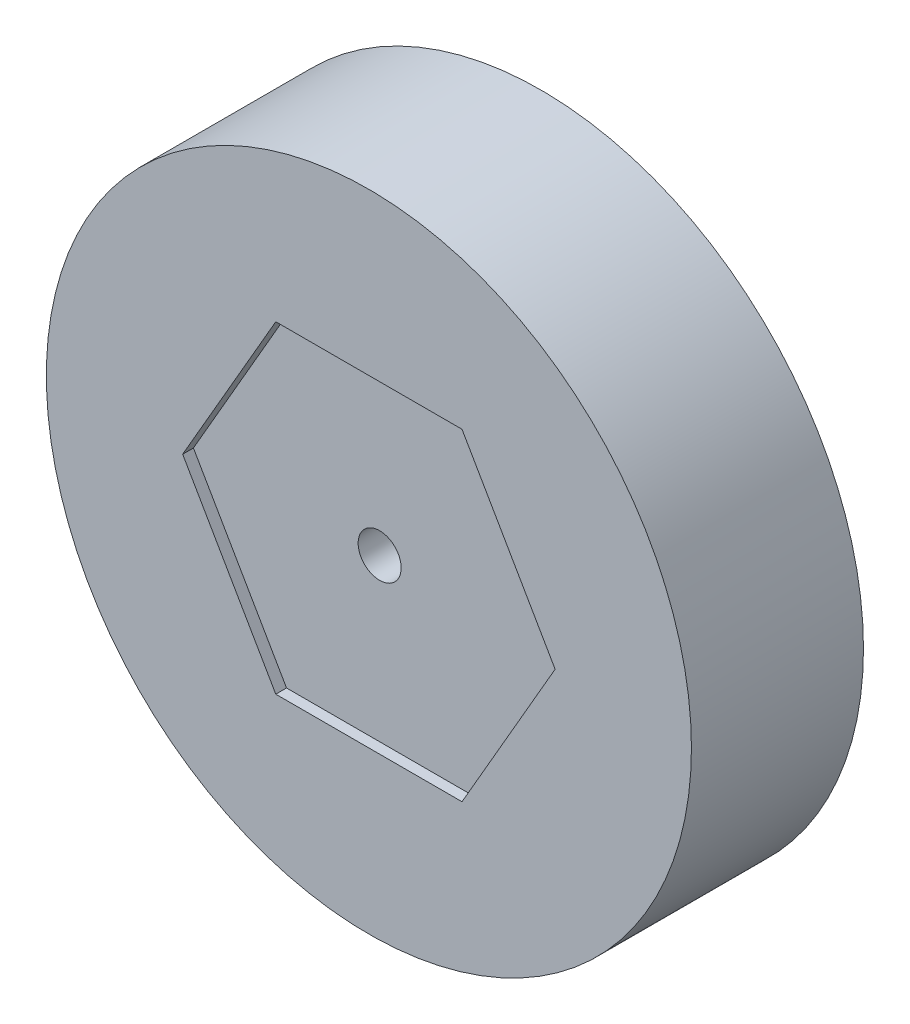
SolidWorks part; units mm, degrees
ref_plane "Front Plane" through (0, 0, 0) normal (0, 0, 1) x (1, 0, 0)
ref_plane "Top Plane" through (0, 0, 0) normal (0, 1, 0) x (1, 0, 0)
ref_plane "Right Plane" through (0, 0, 0) normal (1, 0, 0) x (0, 0, -1)
sketch "Sketch1" plane through (0, 0, 0) normal (0, 0, 1) x (1, 0, 0)
  circle A0 centre (0, 0) radius 15
  circle A1 centre (0, 0) radius 1
  dimension "D1" = 30
  dimension "D2" = 2
extrude "Boss-Extrude1" add sketch "Sketch1" along normal mid plane 8
sketch "Sketch2" plane through (0, 0, 4) normal (0, 0, 1) x (1, 0, 0)
  line L1 (-4.3301, 7.5) -> (-8.6603, 0)
  line L2 (-8.6603, 0) -> (-4.3301, -7.5)
  line L3 (-4.3301, -7.5) -> (4.3301, -7.5)
  line L4 (4.3301, -7.5) -> (8.6603, 0)
  line L5 (8.6603, 0) -> (4.3301, 7.5)
  line L6 (4.3301, 7.5) -> (-4.3301, 7.5)
  circle A0 centre (0, 0) radius 7.5 construction
  dimension "D1" = 15
extrude "Cut-Extrude1" cut sketch "Sketch2" against normal blind 0.5
